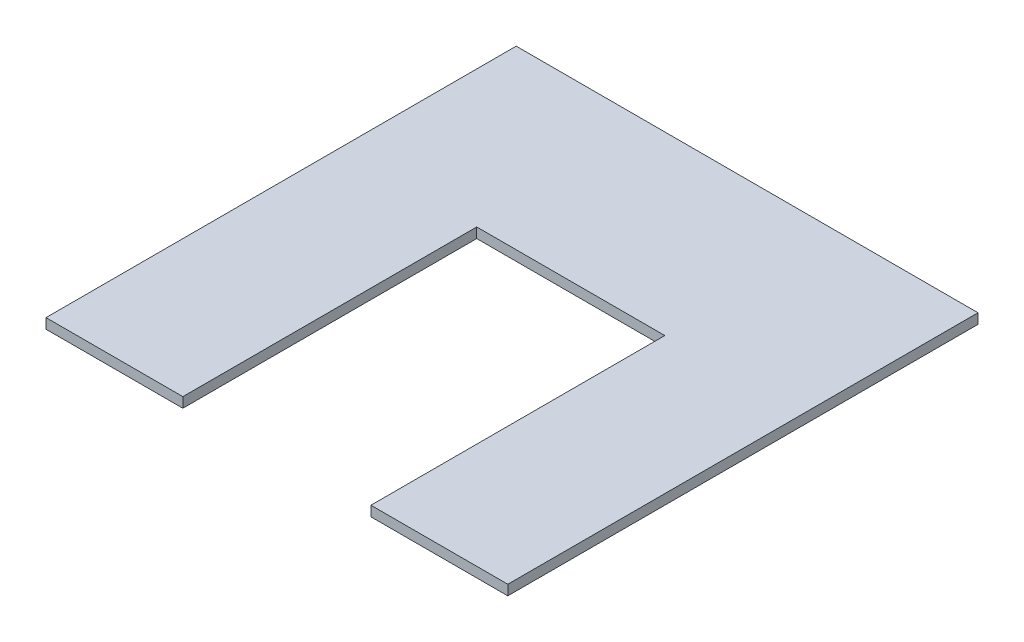
SolidWorks part; units mm, degrees
ref_plane "Front Plane" through (0, 0, 0) normal (0, 0, 1) x (1, 0, 0)
ref_plane "Top Plane" through (0, 0, 0) normal (0, 1, 0) x (1, 0, 0)
ref_plane "Right Plane" through (0, 0, 0) normal (1, 0, 0) x (0, 0, -1)
sketch "Sketch2" plane through (0, 0, 0) normal (0, 1, 0) x (1, 0, 0)
  line L0 (-41.524, 0) -> (233.476, 0)
  line L1 (233.476, 0) -> (233.476, -280)
  line L2 (-41.524, 0) -> (-41.524, -280)
  line L3 (-41.524, -280) -> (39.976, -280)
  line L4 (39.976, -280) -> (39.976, -105)
  line L5 (39.976, -105) -> (151.976, -105)
  line L6 (151.976, -105) -> (151.976, -280)
  line L7 (151.976, -280) -> (233.476, -280)
extrude "Boss-Extrude1" add sketch "Sketch2" along normal blind 6
